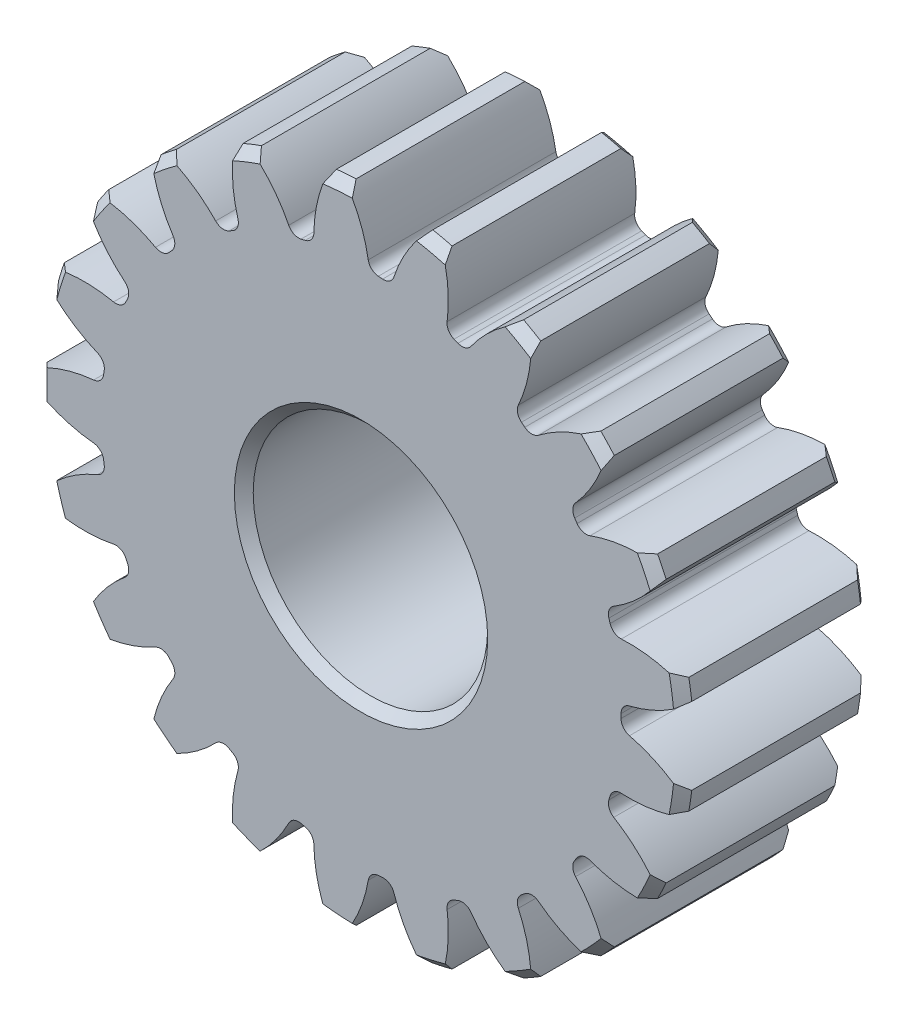
SolidWorks part; units mm, degrees
ref_plane "Front Plane" through (0, 0, 0) normal (0, 0, 1) x (1, 0, 0)
ref_plane "Top Plane" through (0, 0, 0) normal (0, 1, 0) x (1, 0, 0)
ref_plane "Right Plane" through (0, 0, 0) normal (1, 0, 0) x (0, 0, -1)
sketch "Sketch1" plane through (0, 0, 0) normal (0, 0, 1) x (1, 0, 0)
  line L0 (0, 0) -> (0, 3.15) construction
  line L1 (-1.0124, 3.5185) -> (1.0124, 2.7815) construction
  circle A0 centre (0, 0) radius 2.775 construction
  circle A1 centre (0, 0) radius 3.45 construction
  circle A2 centre (0, 0) radius 3.15 construction
  circle A3 centre (0, 0) radius 2.96 construction
  circle A5 centre (0, 0) radius 1.25 construction
  point P8 (0.15, 0)
  point P13 (10.5, 0)
  dimension "OD" = 6.9
  dimension "Root Diameter" = 5.55
  dimension "Gear Pitch Diameter" = 6.3
  dimension "Base Diameter" = 5.9201
  dimension "For Shaft Diameter" = 2.5
  dimension "Pressure Angle" = 20
  dimension "Number of Teeth" = 21
  dimension "Module" = 0.3
sketch "Sketch2" plane through (0, 0, 0) normal (1, 0, 0) x (0, 0, -1)
  line L0 (-1, 0) -> (1, 0) construction
  line L1 (1, 3.45) -> (1, -3.45) construction
  line L3 (-1, 3.45) -> (1, 3.45) construction
  line L5 (-1, 12.5) -> (-1, -12.5) construction
  point P2 (0, 3.45)
  dimension "Overall Width" = 2
  dimension "Face Width" = 1
sketch "Sketch3" plane through (0, 0, 0) normal (0, 0, 1) x (1, 0, 0)
  circle A0 centre (0, 0) radius 3.45
  circle A1 centre (0, 0) radius 3.45 construction
extrude "Boss-Extrude1" add sketch "Sketch3" against normal up to vertex (1 mm away) and the other way up to vertex (1 mm away) up to point (0, 0, -1) other way up to point (0, 0, 1)
sketch "Sketch5" plane through (0, 0, 0) normal (1, 0, 0) x (0, 0, -1)
  line L5 (-1, 0) -> (1, 0)
  line L6 (-1, 0) -> (-1, 1.25)
  line L7 (-1, 1.25) -> (1, 1.25)
  line L8 (1, 0) -> (1, 1.25)
  point P12 (0, 1.25)
revolve "Cut-Revolve1" cut sketch "Sketch5" angle 360 about L0
chamfer "Chamfer2" distance 0.1007 angle 45 4 edges at (3.45, 0, -1) (1.25, 0, -1) (1.25, 0, 1) (3.45, 0, 1)
sketch "Sketch4" plane through (0, 0, 0) normal (0, 0, 1) x (1, 0, 0)
  line L0 (2.7725, -0.1178) -> (2.7725, 0.1178)
  arc A3 (3.4255, 0.41) -> (3.4255, -0.41) centre (0, 0) cw
  circle A4 centre (0, 0) radius 3.45 construction
  arc A5 (3.4255, 0.41) -> (2.7725, 0.1178) centre (2.4963, 1.6108) cw
  circle A6 centre (0, 0) radius 2.775 construction
  arc A7 (3.4255, -0.41) -> (2.7725, -0.1178) centre (2.4963, -1.6108) ccw
  spline S0 degree 4 poles (2.9547, 0.1772) (2.9555, 0.1772) (2.9577, 0.1774) (2.9618, 0.1779) (2.9686, 0.1789) (2.9771, 0.1803) (2.9881, 0.1825) (3.0011, 0.1855) (3.0152, 0.1891) (3.0306, 0.1935) (3.0458, 0.1982) (3.061, 0.2033) (3.076, 0.2086) (3.0942, 0.2155) (3.1158, 0.2242) (3.141, 0.2351) (3.1693, 0.2484) (3.198, 0.2628) (3.226, 0.2777) (3.254, 0.2937) (3.281, 0.3097) (3.3088, 0.3273) (3.3343, 0.3439) (3.3626, 0.3635) (3.3853, 0.3796) (3.415, 0.4018) (3.4324, 0.4153) (3.4526, 0.4313) (3.4616, 0.4387) (3.4671, 0.4432) knots 0 0 0 0 0 0.005377 0.015084 0.028532 0.04661 0.064855 0.092111 0.119476 0.146842 0.174209 0.201575 0.228941 0.256307 0.307035 0.361767 0.4165 0.471232 0.525964 0.580697 0.635429 0.690161 0.744894 0.799626 0.854358 0.909091 0.954545 1 1 1 1 1 construction
  spline S1 degree 4 poles (2.9547, 0.1772) (2.9555, 0.1772) (2.9577, 0.1774) (2.9618, 0.1779) (2.9686, 0.1789) (2.9771, 0.1803) (2.9881, 0.1825) (3.0011, 0.1855) (3.0152, 0.1891) (3.0306, 0.1935) (3.0458, 0.1982) (3.061, 0.2033) (3.076, 0.2086) (3.0942, 0.2155) (3.1158, 0.2242) (3.141, 0.2351) (3.1693, 0.2484) (3.198, 0.2628) (3.226, 0.2777) (3.254, 0.2937) (3.281, 0.3097) (3.3088, 0.3273) (3.3343, 0.3439) (3.3626, 0.3635) (3.3853, 0.3796) (3.4085, 0.397) (3.4198, 0.4056) (3.4255, 0.41) knots 0 0 0 0 0 0.005377 0.015084 0.028532 0.04661 0.064855 0.092111 0.119476 0.146842 0.174209 0.201575 0.228941 0.256307 0.307035 0.361767 0.4165 0.471232 0.525964 0.580697 0.635429 0.690161 0.744894 0.799626 0.854358 0.909091 0.909091 0.909091 0.909091 0.909091 construction
  spline S2 degree 4 poles (2.9547, -0.1772) (2.9555, -0.1772) (2.9577, -0.1774) (2.9618, -0.1779) (2.9686, -0.1789) (2.9771, -0.1803) (2.9881, -0.1825) (3.0011, -0.1855) (3.0152, -0.1891) (3.0306, -0.1935) (3.0458, -0.1982) (3.061, -0.2033) (3.076, -0.2086) (3.0942, -0.2155) (3.1158, -0.2242) (3.141, -0.2351) (3.1693, -0.2484) (3.198, -0.2628) (3.226, -0.2777) (3.254, -0.2937) (3.281, -0.3097) (3.3088, -0.3273) (3.3343, -0.3439) (3.3626, -0.3635) (3.3853, -0.3796) (3.415, -0.4018) (3.4324, -0.4153) (3.4526, -0.4313) (3.4616, -0.4387) (3.4671, -0.4432) knots 0 0 0 0 0 0.005377 0.015084 0.028532 0.04661 0.064855 0.092111 0.119476 0.146842 0.174209 0.201575 0.228941 0.256307 0.307035 0.361767 0.4165 0.471232 0.525964 0.580697 0.635429 0.690161 0.744894 0.799626 0.854358 0.909091 0.954545 1 1 1 1 1 construction
  spline S3 degree 4 poles (2.9547, -0.1772) (2.9555, -0.1772) (2.9577, -0.1774) (2.9618, -0.1779) (2.9686, -0.1789) (2.9771, -0.1803) (2.9881, -0.1825) (3.0011, -0.1855) (3.0152, -0.1891) (3.0306, -0.1935) (3.0458, -0.1982) (3.061, -0.2033) (3.076, -0.2086) (3.0942, -0.2155) (3.1158, -0.2242) (3.141, -0.2351) (3.1693, -0.2484) (3.198, -0.2628) (3.226, -0.2777) (3.254, -0.2937) (3.281, -0.3097) (3.3088, -0.3273) (3.3343, -0.3439) (3.3626, -0.3635) (3.3853, -0.3796) (3.4085, -0.397) (3.4198, -0.4056) (3.4255, -0.41) knots 0 0 0 0 0 0.005377 0.015084 0.028532 0.04661 0.064855 0.092111 0.119476 0.146842 0.174209 0.201575 0.228941 0.256307 0.307035 0.361767 0.4165 0.471232 0.525964 0.580697 0.635429 0.690161 0.744894 0.799626 0.854358 0.909091 0.909091 0.909091 0.909091 0.909091 construction
  dimension "D1" = 0.2356
extrude "Cut-Extrude1" cut sketch "Sketch4" against normal through all both and the other way through all
fillet "Fillet1" radius 0.1178 2 edges at (2.7725, -0.1178, 0) (2.7725, 0.1178, 0)
pattern_circular "CirPattern1" count 21 over 360 about axis through (0, 0, 0) along (0, 0, 1) of "Cut-Extrude1", "Fillet1"
equation "\"Number of Teeth\"= 21"
equation "\"Module\"= 0.3"
equation "\"Diametral Pitch\"= 1 / \"Module\""
equation "\"Dedendum\"= 1.25 / \"Diametral Pitch\""
equation "\"Pitch Diameter\"= \"Module\" * \"Number of Teeth\""
equation "\"Root Diameter\"= \"Pitch Diameter\" - ( 2 * \"Dedendum\" )"
equation "\"Root Diameter@Sketch1\"=\"Root Diameter\""
equation "\"OD@Sketch1\" = \"Outside Diameter\""
equation "\"D1@CirPattern1\"=\"Number of Teeth\""
equation "\"Pressure Angle\"= 20"
equation "\"Base Diameter\"= \"Pitch Diameter\" * cos ( \"Pressure Angle\" )"
equation "\"Outside Diameter\"= ( \"Number of Teeth\" + 2 ) / \"Diametral Pitch\""
equation "\"Pitch Angle\"= 360deg / \"Number of Teeth\""
equation "\"Alpha\"= sqr ( \"Pitch Diameter\" ^ 2 - \"Base Diameter\" ^ 2 ) / \"Base Diameter\" * 180 / PI - \"Pressure Angle\""
equation "\"Beta\"= ( \"Pitch Angle\" / 4 - \"Alpha\" )"
equation "\"Phi\"= sqr ( ( \"Outside Diameter\" / 2 ) ^ 2 - ( \"Base Diameter\" / 2 ) ^ 2 ) / ( \"Base Diameter\" / 2 )"
equation "\"Addendum\"= 1 / \"Diametral Pitch\""
equation "\"WorkingDepth\"= 2 / \"Diametral Pitch\""
equation "\"WholeDepth\"= 2.25 / \"Diametral Pitch\""
equation "\"Clearance\"= 0.25 / \"Diametral Pitch\""
equation "\"ToothThickness\"= ( pi * 2 ) / \"Diametral Pitch\""
equation "\"CircularPitch\"= pi / \"Diametral Pitch\""
equation "\"Number of Teeth@Sketch1\"=\"Number of Teeth\""
equation "\"Module@Sketch1\"=\"Module\""
equation "\"Pressure Angle@Sketch1\"=\"Pressure Angle\""
equation "\"Gear Pitch Diameter@Sketch1\"=\"Pitch Diameter\""
equation "\"Base Diameter@Sketch1\"=\"Base Diameter\""
equation "\"Fillet\"= \"Clearance\" * cos ( \"Pressure Angle\" ) * tan ( ( 90 + \"Pressure Angle\" ) / 2 )"
equation "\"D1\"= \"Fillet\""
equation "\"D1\"= \"Set Screw Pitch@Sketch1\" * .75"
equation "\"D1\"= \"Set Screw Diameter@Sketch1\" / 2"
equation "\"D3\"= \"Set Screw Pitch@Sketch1\" +  ( \"Hub Diameter@Sketch1\" / 2 ) "
equation "\"D4\"= \"Set Screw Pitch@Sketch1\""
equation "\"D2\"= \"Fillet\" * 2"
equation "\"D1\"= \"Fillet\" * 2"
equation "\"D1@Chamfer2\"=\"Fillet\""
equation "\"D1@Sketch4\"=\"CircularPitch\"*0.25"
equation "\"D1@Fillet1\"=\"CircularPitch\"*0.125"
